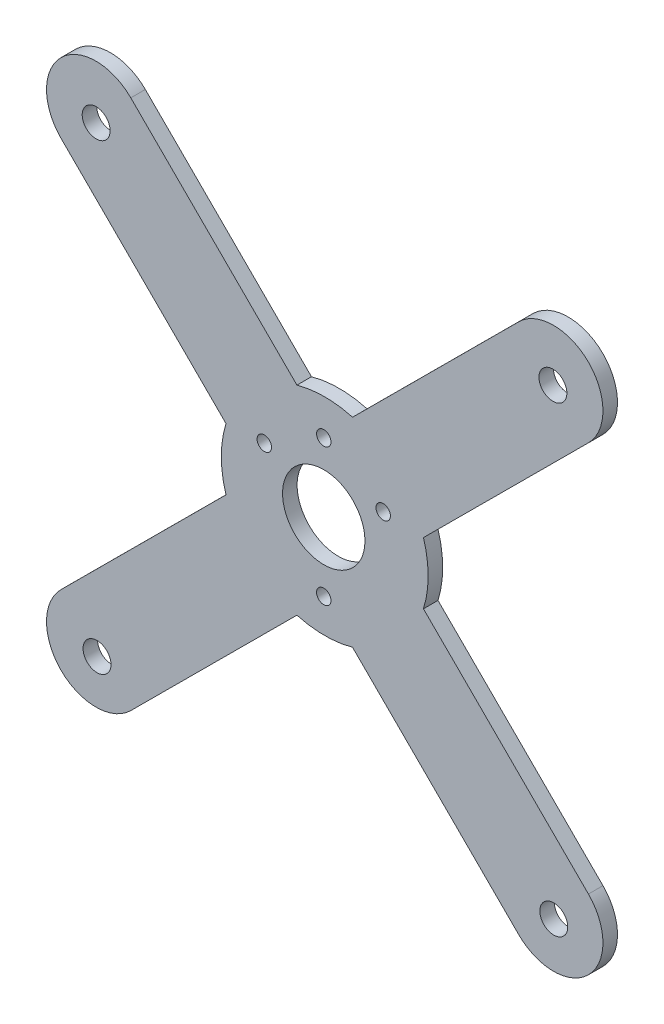
SolidWorks part; units mm, degrees
ref_plane "Front Plane" through (0, 0, 0) normal (0, 0, 1) x (1, 0, 0)
ref_plane "Top Plane" through (0, 0, 0) normal (0, 1, 0) x (1, 0, 0)
ref_plane "Right Plane" through (0, 0, 0) normal (1, 0, 0) x (0, 0, -1)
sketch "Model" plane through (0, 0, 0) normal (0, 0, 1) x (1, 0, 0)
  line L0 (-44.7744, 0.2872) -> (45.1987, 0.2872) construction
  line L1 (-57.3938, 42.9707) -> (-21.354, 7.0263)
  line L2 (-42.155, 58.2499) -> (-5.8596, 22.0506)
  line L3 (-49.7744, 50.6103) -> (0.2122, 0.2872) construction
  line L4 (0.2122, 0.2872) -> (0.2122, 45.6103) construction
  line L5 (57.8181, 42.9707) -> (21.7783, 7.0263)
  line L6 (42.5793, 58.2499) -> (6.284, 22.0506)
  line L7 (57.8181, -42.3963) -> (21.7783, -6.4519)
  line L8 (42.5793, -57.6755) -> (6.284, -21.4762)
  line L9 (-42.155, -57.6755) -> (-5.8596, -21.4762)
  line L10 (-57.3938, -42.3963) -> (-21.354, -6.4519)
  circle A4 centre (0, 15) radius 1.575
  circle A6 centre (-49.7227, 49.7522) radius 3.05
  circle A7 centre (50.0629, 49.996) radius 3.05
  circle A8 centre (50.2504, -50.894) radius 3.05
  circle A9 centre (-49.5349, -51.1415) radius 3.05
  circle A13 centre (-12.99, 7.5) radius 1.575
  circle A14 centre (12.99, 7.5) radius 1.575
  circle A15 centre (0, 0) radius 9
  circle A16 centre (0, -15) radius 1.575
  arc A18 (-21.354, 7.0263) -> (-21.354, -6.4519) centre (0.2122, 0.2872) ccw
  arc A19 (-57.3938, 42.9707) -> (-42.155, 58.2499) centre (-49.7744, 50.6103) cw
  arc A20 (57.8181, 42.9707) -> (42.5793, 58.2499) centre (50.1987, 50.6103) ccw
  arc A21 (57.8181, -42.3963) -> (42.5793, -57.6755) centre (50.1987, -50.0359) cw
  arc A22 (-57.3938, -42.3963) -> (-42.155, -57.6755) centre (-49.7744, -50.0359) ccw
  arc A23 (-5.8596, -21.4762) -> (6.284, -21.4762) centre (0.2122, 0.2872) ccw
  arc A24 (21.7783, -6.4519) -> (21.7783, 7.0263) centre (0.2122, 0.2872) ccw
  arc A25 (6.284, 22.0506) -> (-5.8596, 22.0506) centre (0.2122, 0.2872) ccw
  point P20 (0.2122, 0.2872)
  point P31 (-12.99, 7.5)
  dimension "D1" = 3.15
  dimension "D3" = 18
  dimension "D2" = 12.99
extrude "Boss-Extrude1" add sketch "Model" along normal blind 3.175
